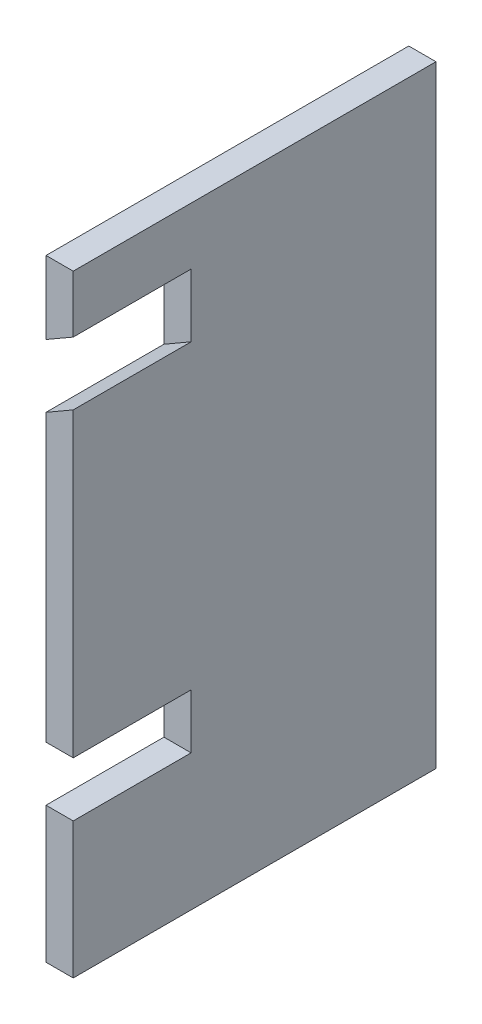
SolidWorks part; units mm, degrees
ref_plane "Front Plane" through (0, 0, 0) normal (0, 0, 1) x (1, 0, 0)
ref_plane "Top Plane" through (0, 0, 0) normal (0, 1, 0) x (1, 0, 0)
ref_plane "Right Plane" through (0, 0, 0) normal (1, 0, 0) x (0, 0, -1)
sketch "Sketch1" plane through (0, 0, 0) normal (0, 0, 1) x (1, 0, 0)
  line L1 (-3, 67.5) -> (3, 67.5)
  line L2 (-3, 67.5) -> (-3, -67.5)
  line L3 (-3, -67.5) -> (3, -67.5)
  line L4 (3, 67.5) -> (3, -67.5)
  line L5 (-3, 67.5) -> (3, -67.5) construction
  line L6 (-3, -67.5) -> (3, 67.5) construction
  point P1 (0, 0)
  dimension "D1" = 6
  dimension "D2" = 135
extrude "Boss-Extrude1" add sketch "Sketch1" along normal blind 80
sketch "Sketch2" plane through (0, 0, 80) normal (0, 0, 1) x (1, 0, 0)
  line L0 (-3, 67.5) -> (-3, -67.5) construction
  line L1 (-3, -25.46) -> (3, -25.46)
  line L2 (-3, -25.46) -> (-3, -37.5)
  line L3 (-3, -37.5) -> (3, -37.5)
  line L4 (3, -25.46) -> (3, -37.5)
  line L5 (3, -67.5) -> (3, 67.5) construction
  line L6 (-3, 37.54) -> (3, 41.0041)
  line L7 (-3, 51.4426) -> (3, 54.9067)
  line L8 (-3, 51.4426) -> (-3, 37.54)
  line L9 (3, 41.0041) -> (3, 54.9067)
  line L10 (-3, -67.5) -> (3, -67.5) construction
  line L11 (-21.0227, 41.0372) -> (22.2511, 66.0213) construction
  line L12 (-15.0027, 30.6103) -> (28.2711, 55.5944) construction
  dimension "D1" = 12.04
  dimension "D2" = 120
  dimension "D4" = 30
  dimension "D5" = 63
  dimension "D3" = 12.04
extrude "Cut-Extrude1" cut sketch "Sketch2" against normal blind 26
